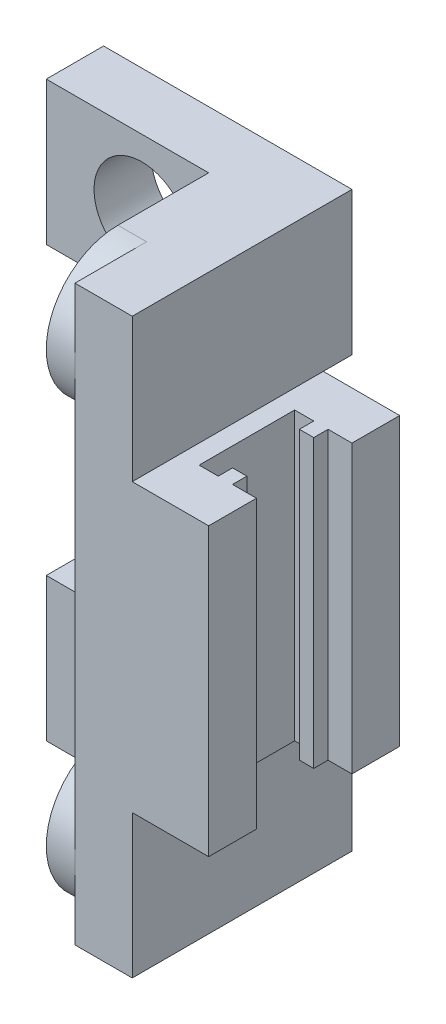
SolidWorks part; units mm, degrees
ref_plane "前视基准面" through (0, 0, 0) normal (0, 0, 1) x (1, 0, 0)
ref_plane "上视基准面" through (0, 0, 0) normal (0, 1, 0) x (1, 0, 0)
ref_plane "右视基准面" through (0, 0, 0) normal (1, 0, 0) x (0, 0, -1)
other "Configuration Table"
sketch "草图1" plane through (0, 0, 0) normal (0, 0, 1) x (1, 0, 0)
  line L0 (-61.0803, 0) -> (61.0803, 0) construction
  line L1 (0, -57.1271) -> (0, 57.1271) construction
  line L3 (3, -30) -> (-3, -30)
  line L4 (3, -30) -> (3, 30)
  line L5 (3, 30) -> (-3, 30)
  line L6 (-3, -30) -> (-3, 30)
  point P4 (0, 0)
  point P8 (0, 0)
extrude "凸台-拉伸1" add sketch "草图1" along normal blind 20 contours L4 L3 L6 L5
sketch "草图2" plane through (3, 0, 0) normal (1, 0, 0) x (0, 0, -1)
  line L0 (-10, 30) -> (-10, -49970) construction
  line L1 (-20, 30) -> (0, 30) construction
  line L2 (-20, -30) -> (0, -30) construction
  line L3 (0, 0) -> (50000, 0) construction
  line L4 (0, -30) -> (0, 30) construction
  line L5 (-15, -15) -> (-20, -15)
  line L6 (-15, 15) -> (-5, 15)
  line L7 (-15, 15) -> (-15, -15)
  line L8 (-15, -15) -> (-5, -15)
  line L9 (-5, 15) -> (-5, -15)
  line L10 (-20, -30) -> (-20, 30) construction
  line L11 (-15, 15) -> (-20, 15)
  line L12 (-20, 15) -> (-20, -15)
  line L13 (-5, -15) -> (0, -15)
  line L14 (-5, 15) -> (0, 15)
  line L15 (-20, -15) -> (-20, 15)
  line L16 (0, -15) -> (0, 15)
  point P4 (-10, 30)
  point P7 (-10, -30)
  point P12 (0, 0)
  line M7 (0, -30) -> (0, 30)
  line M9 (-20, 30) -> (-20, -30)
extrude "凸台-拉伸2" add sketch "草图2" along normal blind 8 contours L7 L11 L5 M9 | L14 L9 L13 M7
sketch "草图3" plane through (3, 0, 0) normal (1, 0, 0) x (0, 0, -1)
  line L1 (-15, 15) -> (-5, 15)
  line L2 (-15, 15) -> (-15, -15)
  line L3 (-15, -15) -> (-5, -15)
  line L4 (-5, 15) -> (-5, -15)
extrude "凸台-拉伸3" add sketch "草图3" along normal blind 2 contours L2 L1 L4 L3
sketch "草图4" plane through (0, -15, 0) normal (0, -1, 0) x (1, 0, 0)
  line L0 (7, 15) -> (7, 13.5)
  line L1 (11, 15) -> (5, 15) construction
  line L2 (7, 13.5) -> (8.5, 13.5)
  line L3 (8.5, 13.5) -> (8.5, 15)
  line L4 (7, 5) -> (7, 6.5)
  line L5 (11, 5) -> (5, 5) construction
  line L6 (7, 6.5) -> (8.5, 6.5)
  line L7 (8.5, 6.5) -> (8.5, 5)
  line L8 (5, 15) -> (5, 5) construction
  line L9 (7, 15) -> (8.5, 15)
  line L10 (7, 5) -> (8.5, 5)
  dimension "D1" = 1.5
  dimension "D2" = 1.5
  dimension "D3" = 1.5
  dimension "D4" = 1.5
  dimension "D5" = 2
extrude "凸台-拉伸4" add sketch "草图4" against normal blind 30 contours L9 L3 L2 L0 | L10 L7 L6 L4
sketch "草图6" plane through (0, 0, 0) normal (0, 0, -1) x (-1, 0, 0)
  line L0 (-3, 15) -> (49997, 15) construction
  line L1 (-3, -15) -> (49997, -15) construction
  line L12 (3, 30) -> (23, 30)
  line L13 (3, 30) -> (3, 15)
  line L14 (3, 15) -> (23, 15)
  line L15 (23, 30) -> (23, 15)
  line L16 (3, -30) -> (23, -30)
  line L17 (3, -30) -> (3, -15)
  line L18 (3, -15) -> (23, -15)
  line L19 (23, -30) -> (23, -15)
  dimension "D1" = 20
  dimension "D2" = 20
  dimension "D3" = 15
extrude "凸台-拉伸5" add sketch "草图6" against normal blind 3
sketch "草图7" plane through (0, 0, 3) normal (0, 0, 1) x (1, 0, 0)
  line L0 (-13, -30) -> (-13, 49970) construction
  line L1 (-3, -30) -> (-23, -30) construction
  line L2 (-23, 30) -> (-3, 30) construction
  line L3 (-3, -22.5) -> (-50003, -22.5) construction
  line L4 (-3, -15) -> (-3, -30) construction
  line L5 (-3, 22.5) -> (-50003, 22.5) construction
  line L6 (-3, 30) -> (-3, 15) construction
  circle A0 centre (-13, -22.5) radius 5
  circle A1 centre (-13, 22.5) radius 5
  point P4 (-13, -30)
  point P7 (-13, 30)
  point P12 (-3, -22.5)
  point P17 (-3, 22.5)
extrude "切除-拉伸1" cut sketch "草图7" against normal through all contours A1 | A0
sketch "草图8" plane through (-3, 0, 0) normal (-1, 0, 0) x (0, 0, 1)
  line L0 (3, 30) -> (3, 15) construction
  line L1 (3, 30) -> (20, 30)
  line L2 (3, 30) -> (3, 15)
  line L3 (3, 15) -> (20, 15)
  line L4 (20, 30) -> (20, 15)
  line L5 (20, 30) -> (3, 30) construction
  line L6 (3, -15) -> (3, -30) construction
  line L7 (3, -15.0817) -> (20, -15.0817)
  line L8 (3, -15.0817) -> (3, -30)
  line L9 (3, -30) -> (20, -30)
  line L10 (20, -15.0817) -> (20, -30)
  line L11 (20, -30) -> (3, -30) construction
  line L12 (20, -30) -> (20, 30) construction
  circle A0 centre (12.5, 22.5) radius 7.5
  circle A1 centre (12.5409, -22.5409) radius 7.4591
  circle A2 centre (12.5, 22.5) radius 5
  circle A3 centre (12.5409, -22.5409) radius 5
  line M12 (3, -15) -> (3, -30)
  line M13 (3, -30) -> (20, -30)
  line M16 (3, 30) -> (3, 15)
extrude "凸台-拉伸7" add sketch "草图8" along normal blind 3 contours A0 A2 | A0 L1 L3 M16 | A1 L7 M12 M13 | A1 A3
sketch "草图10" plane through (-3, 0, 0) normal (-1, 0, 0) x (0, 0, 1)
  circle A0 centre (12.5, 22.5) radius 5
  circle A1 centre (12.5409, -22.5409) radius 5
extrude "切除-拉伸3" cut sketch "草图10" against normal blind 1
sketch "草图11" plane through (0, 0, 0) normal (0, 0, -1) x (-1, 0, 0)
  line L0 (0, 0) -> (0, 50000) construction
  line L1 (0, 0) -> (50000, 0) construction
  line L3 (-3, 30) -> (23, 30)
  line L4 (-3, 30) -> (-3, 15)
  line L5 (-3, 15) -> (23, 15)
  line L6 (23, 30) -> (23, 15)
  line L7 (23, -15) -> (-3, -15)
  line L8 (23, -15) -> (23, -30)
  line L9 (23, -30) -> (-3, -30)
  line L10 (-3, -15) -> (-3, -30)
extrude "凸台-拉伸8" add sketch "草图11" along normal blind 3
sketch "草图12" plane through (0, 0, 0) normal (0, 0, 1) x (1, 0, 0)
  circle A0 centre (-13, 22.5) radius 5
  circle A1 centre (-13, -22.5) radius 5
extrude "切除-拉伸4" cut sketch "草图12" against normal blind 3
